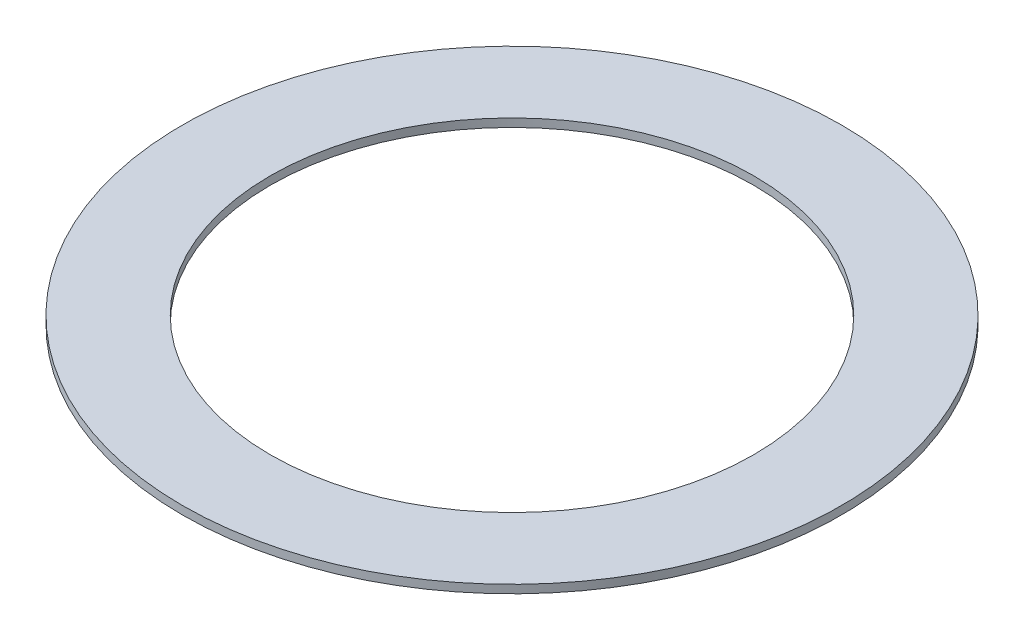
SolidWorks part; units mm, degrees
ref_plane "Front Plane" through (0, 0, 0) normal (0, 0, 1) x (1, 0, 0)
ref_plane "Top Plane" through (0, 0, 0) normal (0, 1, 0) x (1, 0, 0)
ref_plane "Right Plane" through (0, 0, 0) normal (1, 0, 0) x (0, 0, -1)
sketch "Sketch1" plane through (0, 0, 0) normal (0, 1, 0) x (1, 0, 0)
  circle A0 centre (0, 0) radius 8.001
  dimension "D1" = 16.002
extrude "Boss-Extrude1" add sketch "Sketch1" along normal blind 0.2
sketch "Sketch2" plane through (0, 0, 0) normal (0, -1, 0) x (-1, 0, 0)
  circle A0 centre (0, 0) radius 5.8674
  dimension "D1" = 11.7348
extrude "Cut-Extrude1" cut sketch "Sketch2" against normal through all
